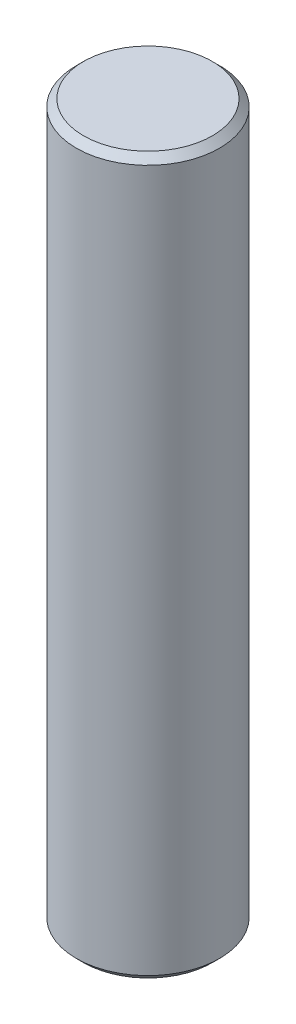
SolidWorks part; units mm, degrees
material "201 Annealed Stainless Steel (SS)"
ref_plane "Front Plane" through (0, 0, 0) normal (0, 0, 1) x (1, 0, 0)
ref_plane "Top Plane" through (0, 0, 0) normal (0, 1, 0) x (1, 0, 0)
ref_plane "Right Plane" through (0, 0, 0) normal (1, 0, 0) x (0, 0, -1)
sketch "Sketch1" plane through (0, 0, 0) normal (0, 1, 0) x (1, 0, 0)
  circle A0 centre (0, 0) radius 2.5
  dimension "Diameter" = 5
extrude "Boss-Extrude1" add sketch "Sketch1" along normal blind 25
chamfer "Chamfer1" distance 0.25 angle 45 2 edges at (0, 0, 2.5) (0, 25, 2.5)
equation "\"Length\"=25"
equation "\"D1@Boss-Extrude1\"=\"Length\""
